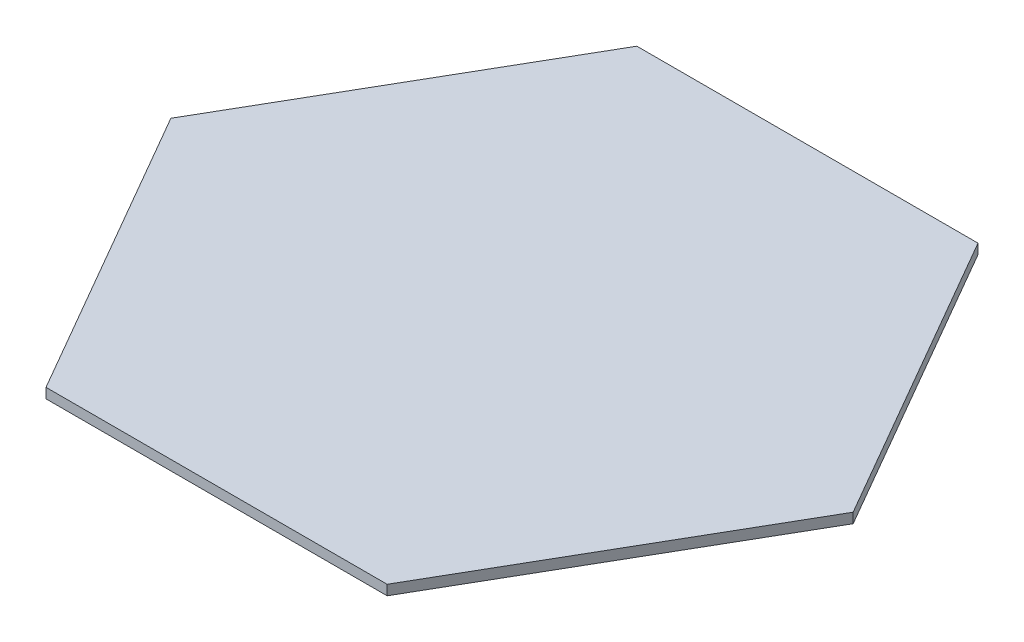
SolidWorks part; units mm, degrees
ref_plane "Front Plane" through (0, 0, 0) normal (0, 0, 1) x (1, 0, 0)
ref_plane "Top Plane" through (0, 0, 0) normal (0, 1, 0) x (1, 0, 0)
ref_plane "Right Plane" through (0, 0, 0) normal (1, 0, 0) x (0, 0, -1)
sketch "Sketch1" plane through (0, 0, 0) normal (0, 1, 0) x (1, 0, 0)
  line L1 (85.25, -147.6573) -> (170.5, 0)
  line L2 (170.5, 0) -> (85.25, 147.6573)
  line L3 (85.25, 147.6573) -> (-85.25, 147.6573)
  line L4 (-85.25, 147.6573) -> (-170.5, 0)
  line L5 (-170.5, 0) -> (-85.25, -147.6573)
  line L6 (-85.25, -147.6573) -> (85.25, -147.6573)
  circle A0 centre (0, 0) radius 147.6573 construction
  dimension "D1" = 170.5
extrude "Boss-Extrude1" add sketch "Sketch1" along normal blind 5
equation "\"side\"= 170.5"
equation "\"D1@Sketch1\"=\"side\""
